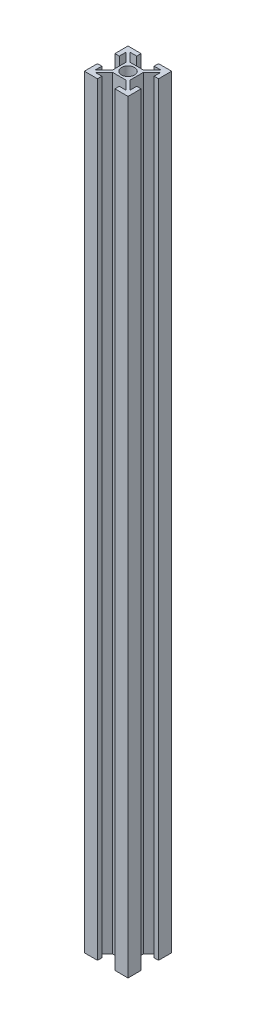
SolidWorks part; units mm, degrees
material "1060 Alloy"
ref_plane "Front Plane" through (0, 0, 0) normal (0, 0, 1) x (1, 0, 0)
ref_plane "Top Plane" through (0, 0, 0) normal (0, 1, 0) x (1, 0, 0)
ref_plane "Right Plane" through (0, 0, 0) normal (1, 0, 0) x (0, 0, -1)
sketch "2020 sketch" plane through (0, 0, 0) normal (0, 1, 0) x (1, 0, 0)
  line L0 (-4, 10) -> (-4, 8)
  line L1 (-10, 10) -> (-4, 10)
  line L2 (-10, 10) -> (-10, 4)
  line L3 (-10, -10) -> (-4, -10)
  line L4 (10, 10) -> (10, 4)
  line L5 (-10, 10) -> (10, -10) construction
  line L6 (-10, -10) -> (10, 10) construction
  line L7 (-4, 8) -> (-7, 8)
  line L8 (-7, 8) -> (-3, 4)
  line L9 (-3, 4) -> (3, 4)
  line L10 (3, 4) -> (7, 8)
  line L11 (7, 8) -> (4, 8)
  line L12 (4, 8) -> (4, 10)
  line L13 (4, 3) -> (4, -3)
  line L14 (8, 7) -> (4, 3)
  line L15 (8, 4) -> (8, 7)
  line L16 (10, 4) -> (8, 4)
  line L17 (8, -4) -> (10, -4)
  line L18 (8, -7) -> (8, -4)
  line L19 (4, -3) -> (8, -7)
  line L20 (3, -4) -> (-3, -4)
  line L21 (7, -8) -> (3, -4)
  line L22 (4, -8) -> (7, -8)
  line L23 (4, -10) -> (4, -8)
  line L24 (-4, -8) -> (-4, -10)
  line L25 (-7, -8) -> (-4, -8)
  line L26 (-3, -4) -> (-7, -8)
  line L27 (-4, -3) -> (-4, 3)
  line L28 (-8, -7) -> (-4, -3)
  line L29 (-8, -4) -> (-8, -7)
  line L30 (-10, -4) -> (-8, -4)
  line L31 (-8, 4) -> (-10, 4)
  line L32 (-8, 7) -> (-8, 4)
  line L33 (-4, 3) -> (-8, 7)
  line L34 (-10, -4) -> (-10, -10)
  line L35 (10, -4) -> (10, -10)
  line L36 (4, 10) -> (10, 10)
  line L37 (4, -10) -> (10, -10)
  circle A0 centre (0, 0) radius 3
  point P0 (0, 0)
  point P14 (4, 9)
  point P42 (0, 0)
  dimension "D9" = 6
  dimension "D1" = 20
  dimension "D2" = 20
  dimension "D3" = 8
  dimension "D4" = 6
  dimension "D5" = 6
  dimension "D6" = 2
  dimension "D7" = 4
  dimension "D8" = 4
extrude "Boss-Extrude1" add sketch "2020 sketch" along normal blind 350 contours A0 | L28 L27 L33 L32 L31 L2 L1 L0 L7 L8 L9 L10 L11 L12 L36 L4 L16 L15 L14 L13 L19 L18 L17 L35 L37 L23 L22 L21 L20 L26 L25 L24 L3 L34 L30 L29
